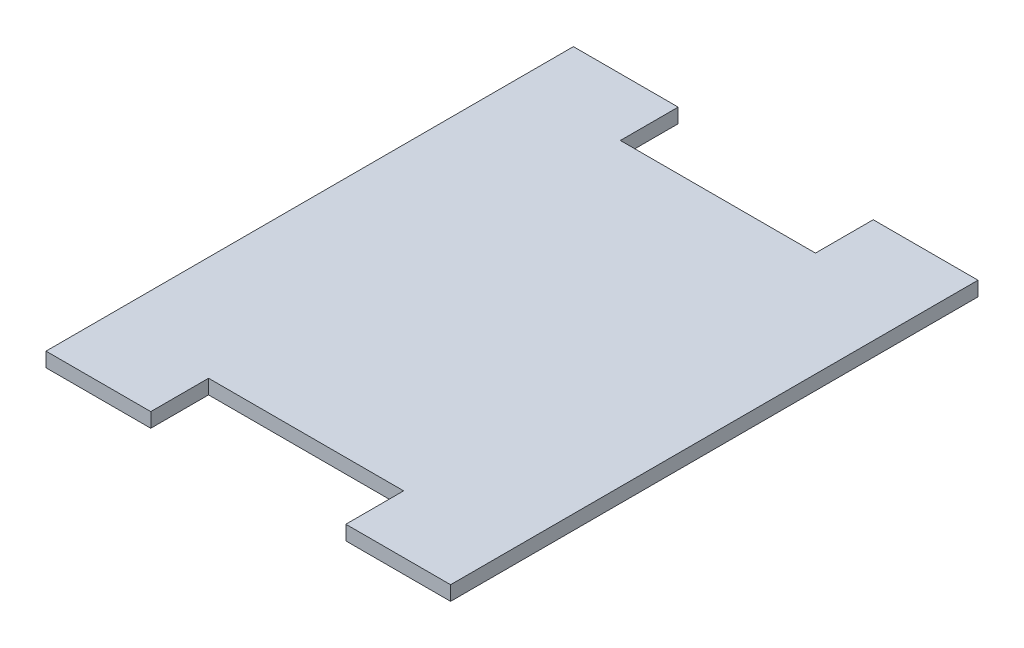
SolidWorks part; units mm, degrees
ref_plane "Front Plane" through (0, 0, 0) normal (0, 0, 1) x (1, 0, 0)
ref_plane "Top Plane" through (0, 0, 0) normal (0, 1, 0) x (1, 0, 0)
ref_plane "Right Plane" through (0, 0, 0) normal (1, 0, 0) x (0, 0, -1)
sketch "Sketch1" plane through (0, 0, 0) normal (0, 1, 0) x (1, 0, 0)
  line L0 (0, 53.7985) -> (0, -37.0746) construction
  line L1 (13.5, 36.0448) -> (-13.5, 36.0448)
  line L2 (-13.5, 36.0448) -> (-13.5, 44.0448)
  line L3 (-13.5, 44.0448) -> (-28, 44.0448)
  line L4 (-28, 44.0448) -> (-28, -28.9552)
  line L5 (-28, -28.9552) -> (-13.5, -28.9552)
  line L6 (-13.5, -28.9552) -> (-13.5, -20.9552)
  line L7 (-13.5, -20.9552) -> (13.5, -20.9552)
  line L8 (13.5, -28.9552) -> (13.5, -20.9552)
  line L9 (28, -28.9552) -> (13.5, -28.9552)
  line L10 (28, 44.0448) -> (28, -28.9552)
  line L11 (13.5, 44.0448) -> (28, 44.0448)
  line L12 (13.5, 36.0448) -> (13.5, 44.0448)
  point P13 (0, -20.9552)
  point P18 (0, 36.0448)
  dimension "D1" = 13.5
  dimension "D2" = 73
  dimension "D3" = 28
  dimension "D4" = 57
extrude "Boss-Extrude1" add sketch "Sketch1" along normal blind 2
